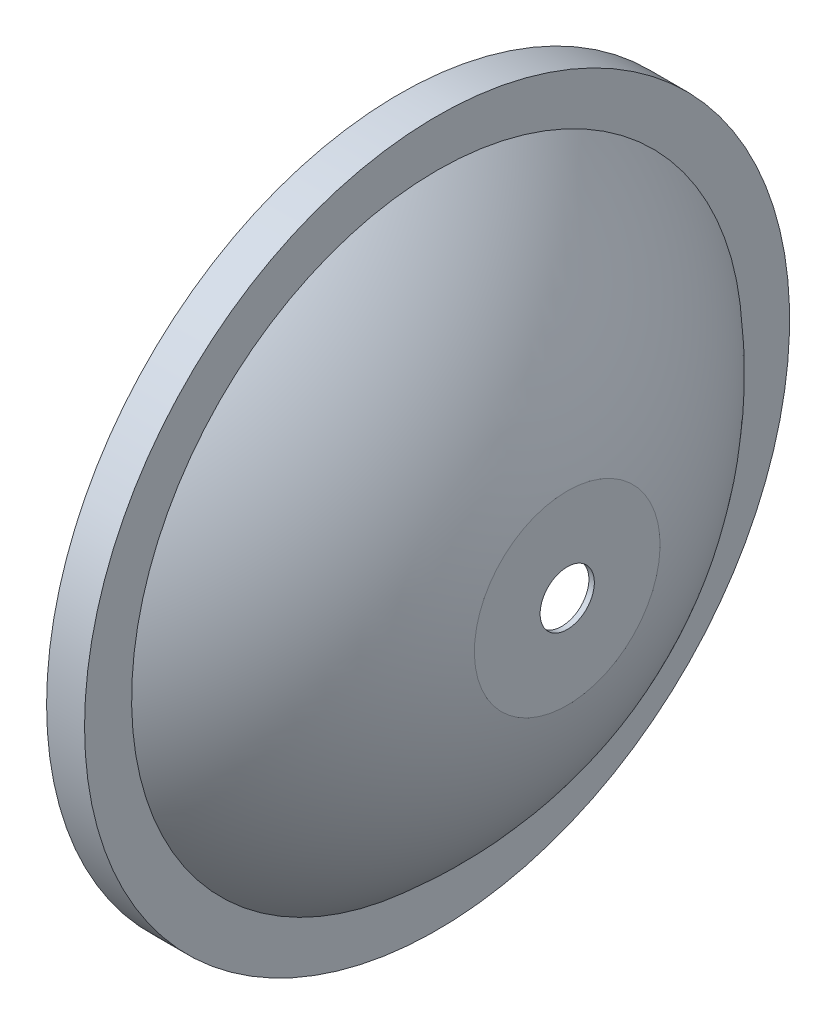
SolidWorks part; units mm, degrees
ref_plane "Front Plane" through (0, 0, 0) normal (0, 0, 1) x (1, 0, 0)
ref_plane "Top Plane" through (0, 0, 0) normal (0, 1, 0) x (1, 0, 0)
ref_plane "Right Plane" through (0, 0, 0) normal (1, 0, 0) x (0, 0, -1)
sketch "Sketch1" plane through (0, 0, 0) normal (0, 0, 1) x (1, 0, 0)
  line L0 (-29.993, 64) -> (-23.993, 64)
  line L1 (-23.993, 64) -> (-23.993, 55.857)
  line L2 (0, 5) -> (0, 17)
  line L3 (-47.3913, 0) -> (27.3913, 0) construction
  line L4 (-29.993, 65) -> (-22.993, 65)
  line L5 (-22.993, 65) -> (-22.993, 56.3205)
  line L6 (1, 5) -> (1, 17.1177)
  line L7 (0, 5) -> (1, 5)
  line L8 (-29.993, 65) -> (-29.993, 64)
  arc A0 (-23.993, 55.857) -> (0, 17) centre (-70.993, 0) cw
  arc A1 (-22.993, 56.3205) -> (1, 17.1177) centre (-70.993, 0) cw
  dimension "D6" = 73
  dimension "D1" = 6
  dimension "D2" = 64
  dimension "D3" = 12
  dimension "D4" = 5
  dimension "D5" = 41
  dimension "D7" = 1
revolve "Revolve1" add sketch "Sketch1" angle 360 about L3
